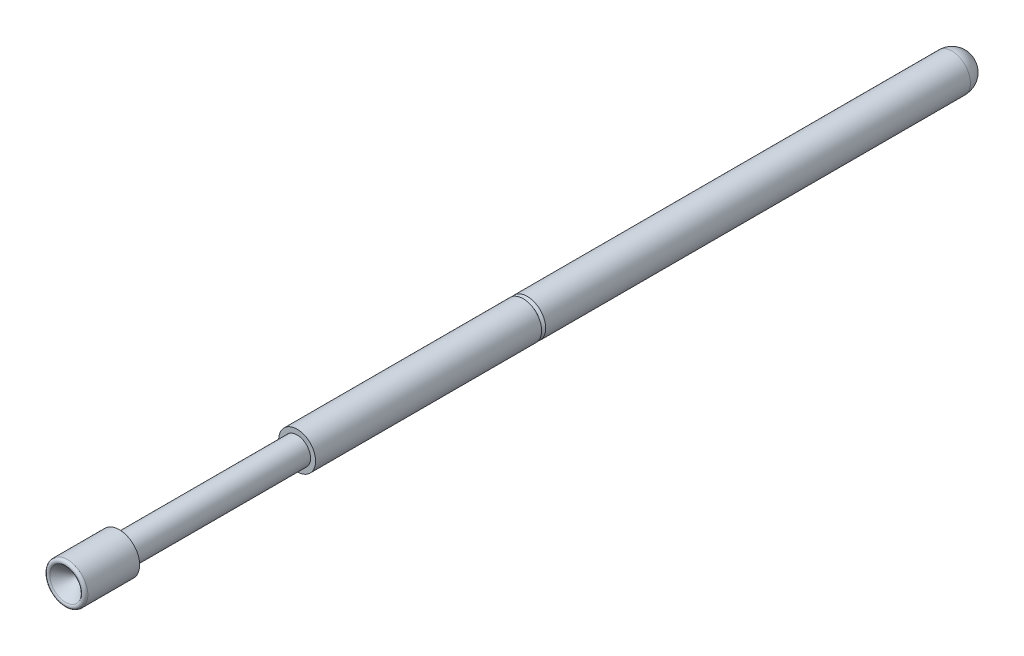
SolidWorks part; units mm, degrees
material "Золото без примесей"
ref_plane "Front" through (0, 0, 0) normal (0, 0, 1) x (1, 0, 0)
ref_plane "Top" through (0, 0, 0) normal (0, 1, 0) x (1, 0, 0)
ref_plane "Right" through (0, 0, 0) normal (1, 0, 0) x (0, 0, -1)
sketch "Эскиз1" plane through (0, 0, 0) normal (0, 1, 0) x (1, 0, 0)
  line L0 (0, 0) -> (0, -66.8671) construction
  line L1 (0, 0) -> (0, -32.749)
  line L2 (0, -32.749) -> (-0.5793, -33.3283)
  line L3 (-0.75, -33.2576) -> (-0.75, -31.35)
  line L4 (-0.75, -31.35) -> (-0.495, -31.35)
  line L5 (-0.495, -31.35) -> (-0.495, -24.8)
  line L6 (-0.495, -24.8) -> (-0.68, -24.8)
  line L7 (-0.68, -24.8) -> (-0.68, -16.475)
  line L8 (-0.68, -16.475) -> (-0.5793, -16.4)
  line L9 (-0.5793, -16.4) -> (-0.68, -16.325)
  line L10 (-0.68, -16.325) -> (-0.68, -0.68)
  line L11 (-0.68, -16.325) -> (-0.68, -16.475) construction
  arc A0 (-0.5793, -33.3283) -> (-0.75, -33.2576) centre (-0.65, -33.2576) cw
  arc A1 (-0.68, -0.68) -> (0, 0) centre (0, -0.68) cw
  point P16 (-0.68, -16.4)
  point P17 (-0.6883, -33.35)
  dimension "D5" = 0.1
  dimension "D1" = 1.36
  dimension "D2" = 33.35
  dimension "D3" = 1.5
  dimension "D4" = 2
  dimension "D6" = 45
  dimension "D7" = 6.55
  dimension "D8" = 0.99
  dimension "D9" = 0.15
  dimension "D10" = 8.4
revolve "Повернуть1" add sketch "Эскиз1" angle 360 about L0
